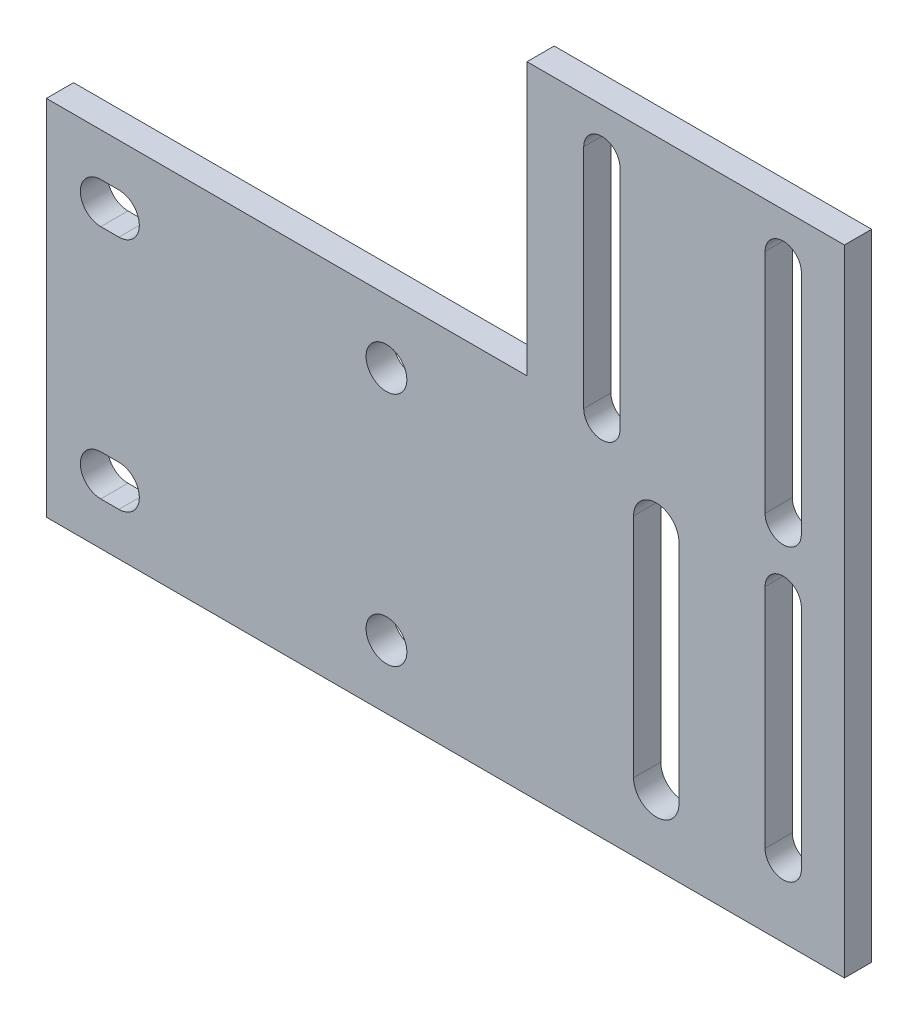
SolidWorks part; units mm, degrees
material "6061 合金"
ref_plane "前视基准面" through (0, 0, 0) normal (0, 0, 1) x (1, 0, 0)
ref_plane "上视基准面" through (0, 0, 0) normal (0, 1, 0) x (1, 0, 0)
ref_plane "右视基准面" through (0, 0, 0) normal (1, 0, 0) x (0, 0, -1)
sketch "草图1" plane through (0, 0, 0) normal (0, 0, 1) x (1, 0, 0)
  line L0 (-14.25, 13) -> (-16.25, 13) construction
  line L1 (-15.25, -13) -> (15.25, -13) construction
  line L2 (-15.25, -13) -> (-15.25, 13) construction
  line L3 (-15.25, 13) -> (15.25, 13) construction
  line L4 (15.25, -13) -> (15.25, 13) construction
  line L5 (-15.25, -13) -> (15.25, 13) construction
  line L6 (-15.25, 13) -> (15.25, -13) construction
  line L7 (-14.25, 10.75) -> (-16.25, 10.75)
  line L8 (-14.25, 15.25) -> (-16.25, 15.25)
  line L9 (-14.25, -13) -> (-16.25, -13) construction
  line L10 (-14.25, -15.25) -> (-16.25, -15.25)
  line L11 (-14.25, -10.75) -> (-16.25, -10.75)
  line L12 (45, 0) -> (45, 16.5575) construction
  line L13 (65.75, -20) -> (-22.25, -20)
  line L14 (65.75, -20) -> (65.75, 20)
  line L16 (-22.25, -20) -> (-22.25, 20)
  line L17 (65.75, -20) -> (-22.25, 20) construction
  line L18 (65.75, 20) -> (-22.25, -20) construction
  line L19 (45, -12.5) -> (45, 12.5) construction
  line L20 (42.5, -12.5) -> (42.5, 12.5)
  line L21 (47.5, -12.5) -> (47.5, 12.5)
  line L23 (30.75, 20) -> (-22.25, 20)
  line L25 (65.75, 20) -> (65.75, 50)
  line L26 (65.75, 50) -> (30.75, 50)
  line L27 (30.75, 20) -> (30.75, 50)
  line L28 (59, 20) -> (59, 45) construction
  line L29 (57, 20) -> (57, 45)
  line L30 (61, 20) -> (61, 45)
  line L31 (61, -12) -> (61, 13)
  line L32 (57, -12) -> (57, 13)
  line L33 (59, -12) -> (59, 13) construction
  line L34 (41, 20) -> (41, 45)
  line L35 (37, 20) -> (37, 45)
  line L36 (39, 20) -> (39, 45) construction
  circle A0 centre (15.25, 13) radius 2.25
  circle A1 centre (15.25, -13) radius 2.25
  arc A2 (-14.25, 10.75) -> (-14.25, 15.25) centre (-14.25, 13) ccw
  arc A3 (-16.25, 15.25) -> (-16.25, 10.75) centre (-16.25, 13) ccw
  arc A4 (-14.25, -15.25) -> (-14.25, -10.75) centre (-14.25, -13) ccw
  arc A5 (-16.25, -10.75) -> (-16.25, -15.25) centre (-16.25, -13) ccw
  arc A6 (42.5, -12.5) -> (47.5, -12.5) centre (45, -12.5) ccw
  arc A7 (47.5, 12.5) -> (42.5, 12.5) centre (45, 12.5) ccw
  arc A13 (57, 20) -> (61, 20) centre (59, 20) ccw
  arc A14 (61, 45) -> (57, 45) centre (59, 45) ccw
  arc A15 (57, -12) -> (61, -12) centre (59, -12) ccw
  arc A16 (61, 13) -> (57, 13) centre (59, 13) ccw
  arc A17 (37, 20) -> (41, 20) centre (39, 20) ccw
  arc A18 (41, 45) -> (37, 45) centre (39, 45) ccw
  point P0 (0, 0)
  point P10 (-15.25, 13)
  point P17 (-15.25, -13)
  point P22 (-15.25, 10.75)
  point P23 (-15.25, -10.75)
  point P24 (17, 0)
  point P33 (45, 0)
  point P45 (59, 0.5)
  point P48 (21.75, 0)
  point P52 (59, 32.5)
  point P64 (39, 32.5)
  dimension "D3" = 4.5
  dimension "D4" = 4.5
  dimension "D6" = 88
  dimension "D15" = 2.5
  dimension "D12" = 2
  dimension "D16" = 20
  dimension "D25" = 2
  dimension "D1" = 30.5
  dimension "D2" = 26
  dimension "D5" = 4.5
  dimension "D7" = 2
  dimension "D8" = 4.5
  dimension "D9" = 2
  dimension "D10" = 40
  dimension "D11" = 17
  dimension "D13" = 45
  dimension "D14" = 25
  dimension "D17" = 14
  dimension "D18" = 20
  dimension "D20" = 7
  dimension "D21" = 30
  dimension "D22" = 35
  dimension "D23" = 13.75
  dimension "D24" = 25
  dimension "D26" = 32
  dimension "D27" = 2
extrude "凸台-拉伸1" add sketch "草图1" along normal blind 3
